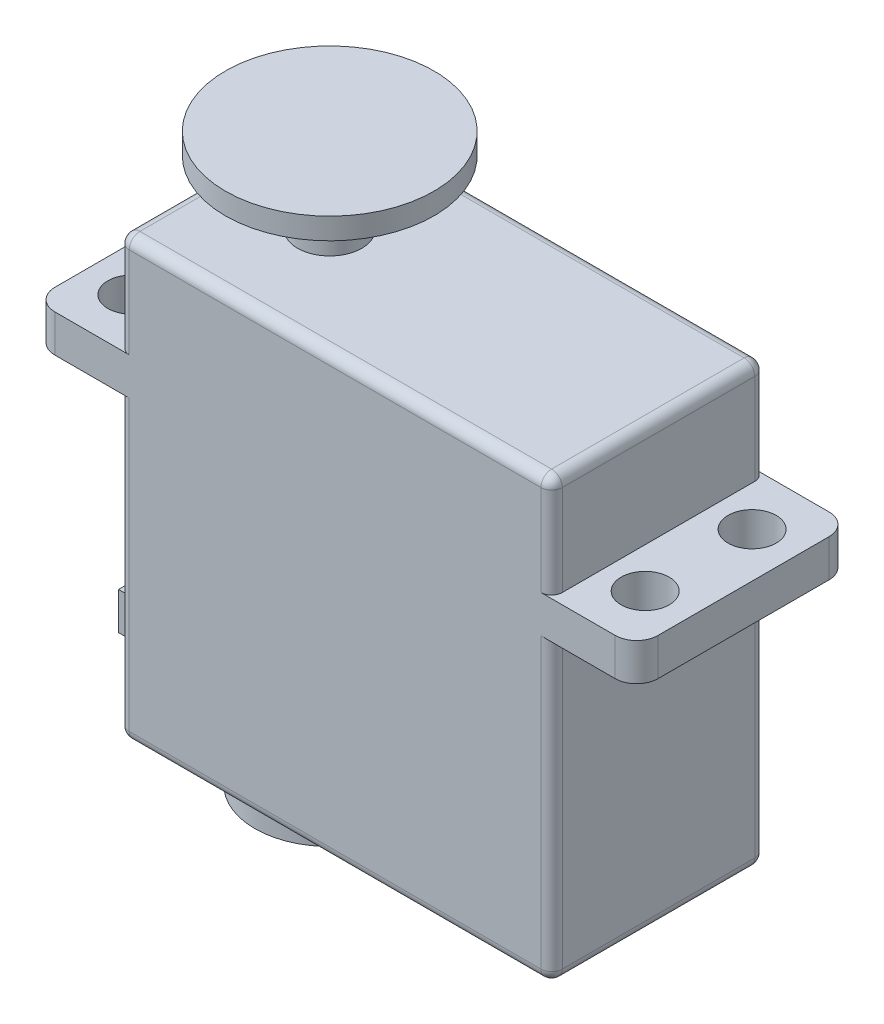
SolidWorks part; units mm, degrees
ref_plane "Front Plane" through (0, 0, 0) normal (0, 0, 1) x (1, 0, 0)
ref_plane "Top Plane" through (0, 0, 0) normal (0, 1, 0) x (1, 0, 0)
ref_plane "Right Plane" through (0, 0, 0) normal (1, 0, 0) x (0, 0, -1)
sketch "Sketch1" plane through (0, 0, 0) normal (0, 1, 0) x (1, 0, 0)
  line L1 (-20.25, 10) -> (20.25, 10)
  line L2 (-20.25, 10) -> (-20.25, -10)
  line L3 (-20.25, -10) -> (20.25, -10)
  line L4 (20.25, 10) -> (20.25, -10)
  line L5 (-20.25, 10) -> (20.25, -10) construction
  line L6 (-20.25, -10) -> (20.25, 10) construction
  point P0 (0, 0)
  dimension "D1" = 40.5
  dimension "D2" = 20
extrude "Boss-Extrude1" add sketch "Sketch1" along normal blind 41
ref_plane "Plane1" through (0, 28, 0) normal (0, -1, 0) x (-1, 0, 0)
sketch "Sketch2" plane through (0, 28, 0) normal (0, -1, 0) x (-1, 0, 0)
  line L1 (28.2, -10) -> (-28.2, -10)
  line L2 (28.2, -10) -> (28.2, 10)
  line L3 (28.2, 10) -> (-28.2, 10)
  line L4 (-28.2, -10) -> (-28.2, 10)
  line L5 (28.2, -10) -> (-28.2, 10) construction
  line L6 (28.2, 10) -> (-28.2, -10) construction
  line L7 (24, -5) -> (-24, -5) construction
  line L8 (24, -5) -> (24, 5) construction
  line L9 (24, 5) -> (-24, 5) construction
  line L10 (-24, -5) -> (-24, 5) construction
  line L11 (24, -5) -> (-24, 5) construction
  line L12 (24, 5) -> (-24, -5) construction
  circle A0 centre (-24, 5) radius 2.25
  circle A1 centre (24, 5) radius 2.25
  circle A2 centre (24, -5) radius 2.25
  circle A3 centre (-24, -5) radius 2.25
  point P0 (0, 0)
  point P6 (0, 0)
  dimension "D5" = 4.5
  dimension "D1" = 56.4
  dimension "D2" = 20
  dimension "D3" = 10
  dimension "D4" = 48
extrude "Boss-Extrude2" add sketch "Sketch2" against normal blind 3.5
sketch "Sketch3" plane through (0, 41, 0) normal (0, 1, 0) x (1, 0, 0)
  line L0 (-20.25, -10) -> (-20.25, 10) construction
  circle A0 centre (-10.5, 0) radius 3
  dimension "D3" = 6
  dimension "D1" = 0
  dimension "D2" = 9.75
extrude "Boss-Extrude3" add sketch "Sketch3" along normal blind 6
sketch "Sketch4" plane through (-20.25, 0, 0) normal (-1, 0, 0) x (0, 0, 1)
  line L0 (-10, 0) -> (10, 0) construction
  line L1 (5, 3.5) -> (-5, 3.5)
  line L2 (5, 3.5) -> (5, 7)
  line L3 (5, 7) -> (-5, 7)
  line L4 (-5, 3.5) -> (-5, 7)
  line L5 (5, 3.5) -> (-5, 7) construction
  line L6 (5, 7) -> (-5, 3.5) construction
  point P0 (0, 5.25)
  dimension "D1" = 10
  dimension "D2" = 3.5
  dimension "D3" = 0
  dimension "D4" = 3.5
extrude "Boss-Extrude4" add sketch "Sketch4" along normal blind 5
fillet "Fillet1" radius 2 4 edges at (28.2, 29.75, -10) (28.2, 29.75, 10) (-28.2, 29.75, -10) (-28.2, 29.75, 10)
fillet "Fillet2" radius 1 10 edges at (0, 0, -10) (-20.25, 0, 0) (0, 0, 10) (20.25, 0, 0) (20.25, 14, 10) (20.25, 14, -10) (-20.25, 36.25, -10) (-20.25, 14, -10) (-20.25, 14, 10) (-20.25, 36.25, 10)
fillet "Fillet3" radius 1 8 edges at (0.5, 41, 10) (-19.9571, 41, 9.7071) (-20.25, 41, 0) (-19.9571, 41, -9.7071) (20.25, 41, 0) (0.5, 41, -10) (20.25, 36.25, -10) (20.25, 36.25, 10)
ref_plane "Plane2" through (0, 22.25, 0) normal (0, -1, 0) x (-1, 0, 0)
sketch "Sketch5" plane through (0, 47, 0) normal (0, 1, 0) x (1, 0, 0)
  circle A0 centre (-10.5, 0) radius 9.75
  dimension "D1" = 19.5
extrude "Boss-Extrude5" add sketch "Sketch5" along normal blind 2
sketch "Sketch6" plane through (0, 0, 0) normal (0, -1, 0) x (1, 0, 0)
  line L0 (-20.25, 9) -> (-20.25, -9) construction
  line L1 (-19.25, 10) -> (19.25, 10) construction
  circle A0 centre (-10.5, 0) radius 7
  circle A1 centre (-10.5, 0) radius 4
  dimension "D1" = 14
  dimension "D4" = 8
  dimension "D2" = 9.75
  dimension "D3" = 10
extrude "Boss-Extrude6" add sketch "Sketch6" along normal blind 4
